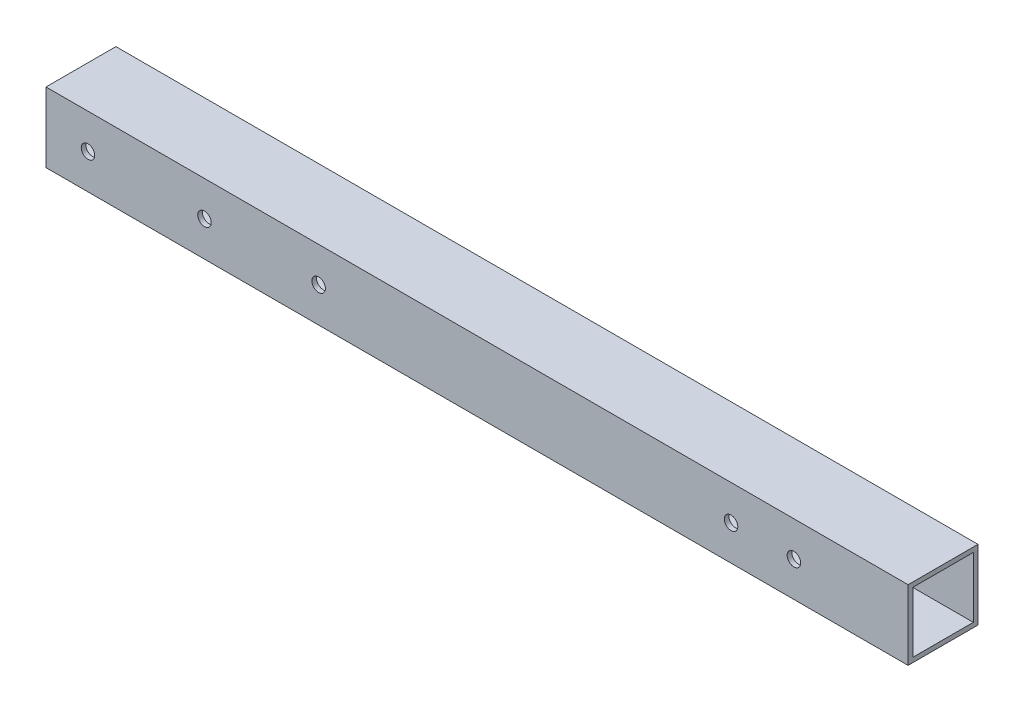
SolidWorks part; units mm, degrees
material "Thornel Mat VMA"
ref_plane "前视基准面" through (0, 0, 0) normal (0, 0, 1) x (1, 0, 0)
ref_plane "上视基准面" through (0, 0, 0) normal (0, 1, 0) x (1, 0, 0)
ref_plane "右视基准面" through (0, 0, 0) normal (1, 0, 0) x (0, 0, -1)
other "Configuration Table"
sketch "草图1" plane through (0, 0, 0) normal (1, 0, 0) x (0, 0, -1)
  line L0 (-6.5, -6.5) -> (-6.5, 6.5)
  line L1 (-7.5, -7.5) -> (7.5, -7.5)
  line L2 (-7.5, -7.5) -> (-7.5, 7.5)
  line L3 (-7.5, 7.5) -> (7.5, 7.5)
  line L4 (7.5, -7.5) -> (7.5, 7.5)
  line L5 (-7.5, -7.5) -> (7.5, 7.5) construction
  line L6 (-7.5, 7.5) -> (7.5, -7.5) construction
  line L7 (-6.5, 6.5) -> (6.5, 6.5)
  line L8 (6.5, -6.5) -> (6.5, 6.5)
  line L9 (-6.5, -6.5) -> (6.5, -6.5)
  point P0 (0, 0)
  dimension "D1" = 15
  dimension "D2" = 15
  dimension "D3" = 1
extrude "凸台-拉伸1" add sketch "草图1" along normal blind 185
sketch "草图2" plane through (0, 0, -7.5) normal (0, 0, -1) x (-1, 0, 0)
  circle A0 centre (-9.0104, 0) radius 1.45 construction
  circle A1 centre (-9.0104, 0) radius 1.45
  circle A2 centre (-160.5, 0) radius 1.45 construction
  circle A3 centre (-147, 0) radius 1.45 construction
  circle A4 centre (-58.5, 0) radius 1.45 construction
  circle A5 centre (-34.0104, 0) radius 1.45 construction
  circle A6 centre (-160.5, 0) radius 1.45
  circle A7 centre (-147, 0) radius 1.45
  circle A8 centre (-58.5, 0) radius 1.45
  circle A9 centre (-34.0104, 0) radius 1.45
extrude "切除-拉伸1" cut sketch "草图2" against normal through all
